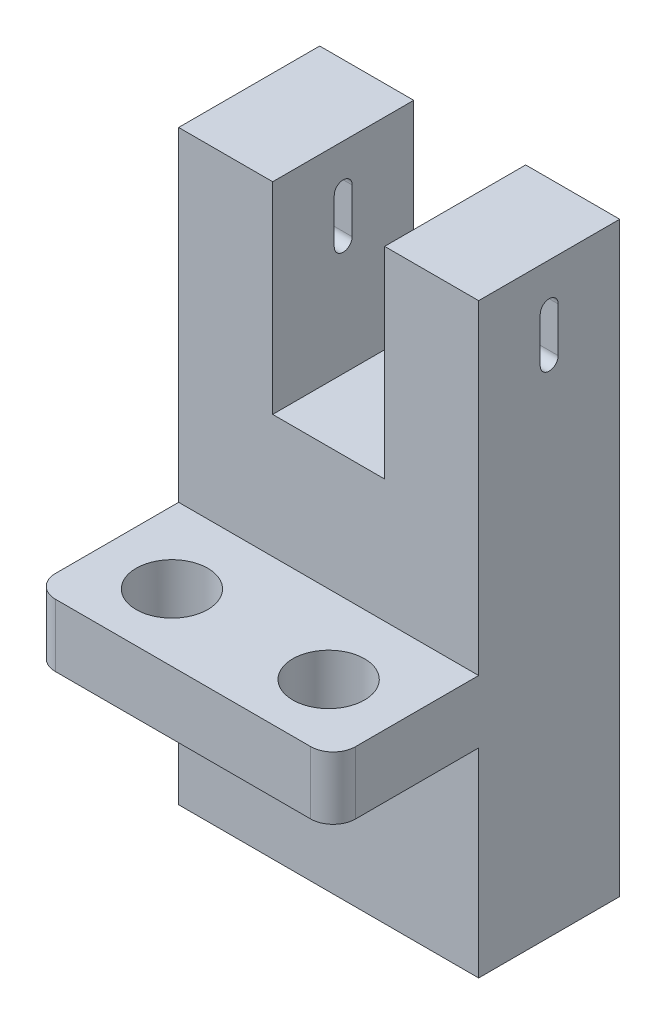
SolidWorks part; units mm, degrees
ref_plane "前视基准面" through (0, 0, 0) normal (0, 0, 1) x (1, 0, 0)
ref_plane "上视基准面" through (0, 0, 0) normal (0, 1, 0) x (1, 0, 0)
ref_plane "右视基准面" through (0, 0, 0) normal (1, 0, 0) x (0, 0, -1)
sketch "草图1" plane through (0, 0, 0) normal (1, 0, 0) x (0, 0, -1)
  line L0 (-37.6682, 0) -> (53.9589, 0) construction
  line L1 (0, 30.3959) -> (0, -33.8757) construction
  line L2 (3.15, 0) -> (-3.15, 0)
  line L3 (-3.15, 0) -> (-3.15, 8.9)
  line L4 (-3.15, 8.9) -> (-9.65, 8.9)
  line L5 (-9.65, 8.9) -> (-9.65, 11.7)
  line L6 (-9.65, 11.7) -> (-3.15, 11.7)
  line L7 (-3.15, 11.7) -> (-3.15, 26.2)
  line L8 (-3.15, 26.2) -> (3.15, 26.2)
  line L9 (3.15, 26.2) -> (3.15, 0)
  point P14 (0, 26.2)
  point P15 (0, 0)
  dimension "D1" = 26.2
  dimension "D2" = 6.3
  dimension "D3" = 2.8
  dimension "D4" = 8.9
  dimension "D5" = 6.5
extrude "凸台-拉伸1" add sketch "草图1" along normal mid plane 13.4
sketch "草图2" plane through (0, 0, 0) normal (0, 0, 1) x (1, 0, 0)
  line L0 (0, -0.7481) -> (0, 32.011) construction
  line L1 (2.5, 26.2) -> (-2.5, 26.2)
  line L2 (6.7, 26.2) -> (-6.7, 26.2) construction
  line L3 (-2.5, 26.2) -> (-2.5, 17.2)
  line L4 (-2.5, 17.2) -> (2.5, 17.2)
  line L5 (2.5, 26.2) -> (2.5, 17.2)
  point P10 (0, 17.2)
  point P11 (0, 26.2)
  dimension "D1" = 5
  dimension "D2" = 9
extrude "切除-拉伸1" cut sketch "草图2" against normal through all both and the other way through all
fillet "圆角1" radius 1 2 edges at (6.7, 10.3, 9.65) (-6.7, 10.3, 9.65)
sketch "草图3" plane through (0, 11.7, 0) normal (0, 1, 0) x (1, 0, 0)
  line L0 (0, 6.6422) -> (0, -12.7864) construction
  line L1 (-10.495, 0) -> (8.4593, 0) construction
  line L2 (-9.8428, -6.65) -> (10.1195, -6.65) construction
  line L3 (6.7, -3.15) -> (-6.7, -3.15) construction
  circle A0 centre (3.5, -6.65) radius 1.6
  circle A1 centre (-3.5, -6.65) radius 1.6
  dimension "D2" = 3.2
  dimension "D1" = 3.5
  dimension "D3" = 7
extrude "切除-拉伸2" cut sketch "草图3" against normal blind 13.4
sketch "草图4" plane through (6.7, 0, 0) normal (1, 0, 0) x (0, 0, -1)
  line L0 (0, -1.2164) -> (0, 26.6906) construction
  line L1 (0, 24.3) -> (0, 22.3) construction
  line L2 (0.4, 24.3) -> (0.4, 22.3)
  line L3 (-0.4, 24.3) -> (-0.4, 22.3)
  line L4 (-8.65, 8.9) -> (-3.15, 8.9) construction
  arc A0 (0.4, 24.3) -> (-0.4, 24.3) centre (0, 24.3) ccw
  arc A1 (-0.4, 22.3) -> (0.4, 22.3) centre (0, 22.3) ccw
  point P5 (0, 23.3)
  dimension "D1" = 0.8
  dimension "D2" = 2
  dimension "D3" = 14.4
extrude "切除-拉伸3" cut sketch "草图4" against normal through all
